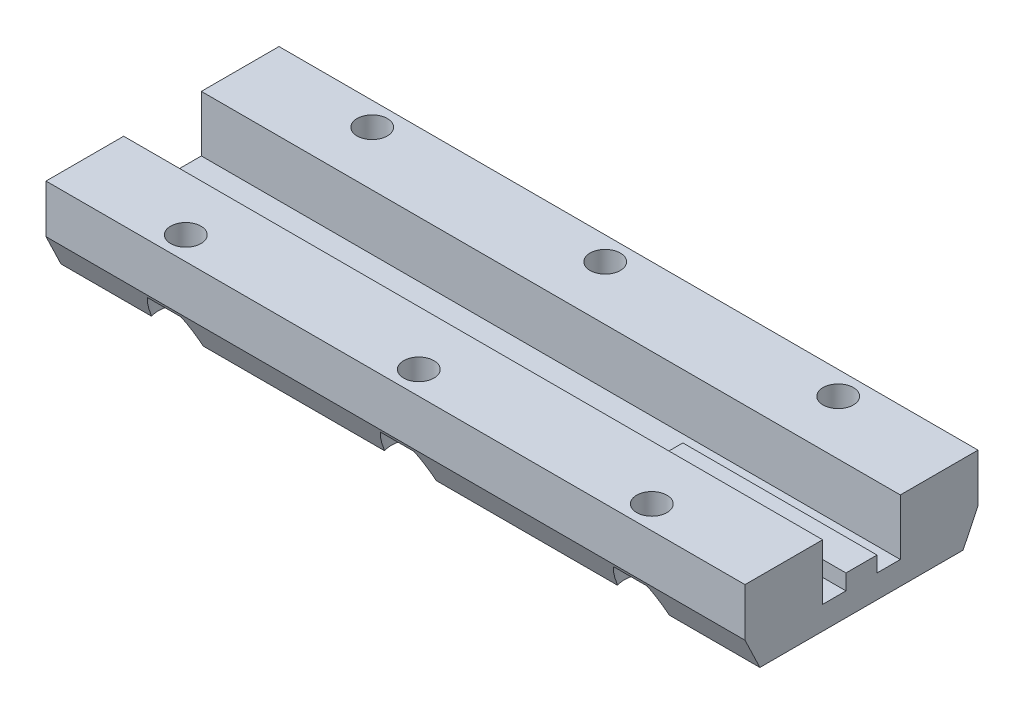
SolidWorks part; units mm, degrees
ref_plane "정면" through (0, 0, 0) normal (0, 0, 1) x (1, 0, 0)
ref_plane "윗면" through (0, 0, 0) normal (0, 1, 0) x (1, 0, 0)
ref_plane "우측면" through (0, 0, 0) normal (1, 0, 0) x (0, 0, -1)
sketch "스케치1" plane through (0, 0, 0) normal (1, 0, 0) x (0, 0, -1)
  line L0 (0, 0) -> (0, -19.6739) construction
  line L1 (0, 0) -> (-29.5436, 0) construction
  line L2 (-15, 0) -> (-15, -6.2)
  line L3 (-5, 0) -> (-5, -7.2)
  line L4 (-5, -7.2) -> (-1.95, -7.2)
  line L5 (-1.95, -7.2) -> (-1.95, -10.2)
  line L6 (-1.95, -10.2) -> (-13.0811, -10.2)
  line L7 (-13.0811, -10.2) -> (-15, -6.2)
  line L8 (-15, 0) -> (-5, 0)
  line L9 (13.0811, -10.2) -> (15, -6.2)
  line L10 (15, 0) -> (5, 0)
  line L11 (1.95, -10.2) -> (13.0811, -10.2)
  line L12 (1.95, -7.2) -> (1.95, -10.2)
  line L13 (5, -7.2) -> (1.95, -7.2)
  line L14 (5, 0) -> (5, -7.2)
  line L15 (15, 0) -> (15, -6.2)
  line L16 (-10, 0) -> (-25.4, 0) construction
  dimension "D1" = 7.2
  dimension "D2" = 5
  dimension "D3" = 3
  dimension "D4" = 10
  dimension "D5" = 3.9
extrude "보스-돌출1" add sketch "스케치1" along normal blind 90
sketch "스케치3" plane through (0, -10.2, 0) normal (0, -1, 0) x (1, 0, 0)
  line L0 (15, 12) -> (45, 12) construction
  line L1 (45, 12) -> (75, 12) construction
  line L2 (75, 12) -> (110, 12) construction
  line L3 (0, 13.0811) -> (0, 1.95) construction
  line L5 (0, 0) -> (166.614, 0) construction
  circle A0 centre (15, 12) radius 1.95
  circle A1 centre (45, 12) radius 1.95
  circle A2 centre (110, 12) radius 1.95 construction
  circle A3 centre (75, 12) radius 1.95
  circle A4 centre (110, -12) radius 1.95
  circle A5 centre (75, -12) radius 1.95
  circle A6 centre (45, -12) radius 1.95
  circle A7 centre (15, -12) radius 1.95
  line M18 (0, -13.0811) -> (90, -13.0811)
  dimension "D1" = 3.9
  dimension "D2" = 3.9
  dimension "D3" = 3.9
  dimension "D4" = 3.9
  dimension "D5" = 30
  dimension "D6" = 30
  dimension "D7" = 35
  dimension "D8" = 15
  dimension "D9" = 12
extrude "컷-돌출1" cut sketch "스케치3" against normal through all contours A0 | A7 | A6 | A5 | A4 | A2 | A3 | A1 | A7 M18 | A6 M18 | A5 M18
sketch "스케치5" plane through (0, 0, 0) normal (0, 0, 1) x (1, 0, 0)
  line L0 (90, -10.2) -> (76.6229, -10.2) construction
  line L1 (65, -5.2) -> (90, -5.2)
  line L2 (65, -5.2) -> (65, -10.2)
  line L3 (65, -10.2) -> (90, -10.2)
  line L4 (90, -5.2) -> (90, -10.2)
  line L5 (90, -6.2) -> (90, -10.2) construction
  dimension "D1" = 25
  dimension "D2" = 5
extrude "보스-돌출2" add sketch "스케치5" along normal mid plane 4
sketch "스케치6" plane through (0, -10.2, 0) normal (0, -1, 0) x (1, 0, 0)
  circle A0 centre (15, 12) radius 3.5
  circle A1 centre (15, -12) radius 3.5
  circle A2 centre (45, 12) radius 3.5
  circle A3 centre (75, 12) radius 3.5
  circle A4 centre (75, -12) radius 3.5
  circle A5 centre (45, -12) radius 3.5
  dimension "D1" = 7
  dimension "D2" = 7
  dimension "D3" = 7
  dimension "D4" = 7
  dimension "D5" = 7
  dimension "D6" = 7
extrude "컷-돌출2" cut sketch "스케치6" against normal blind 3.5
